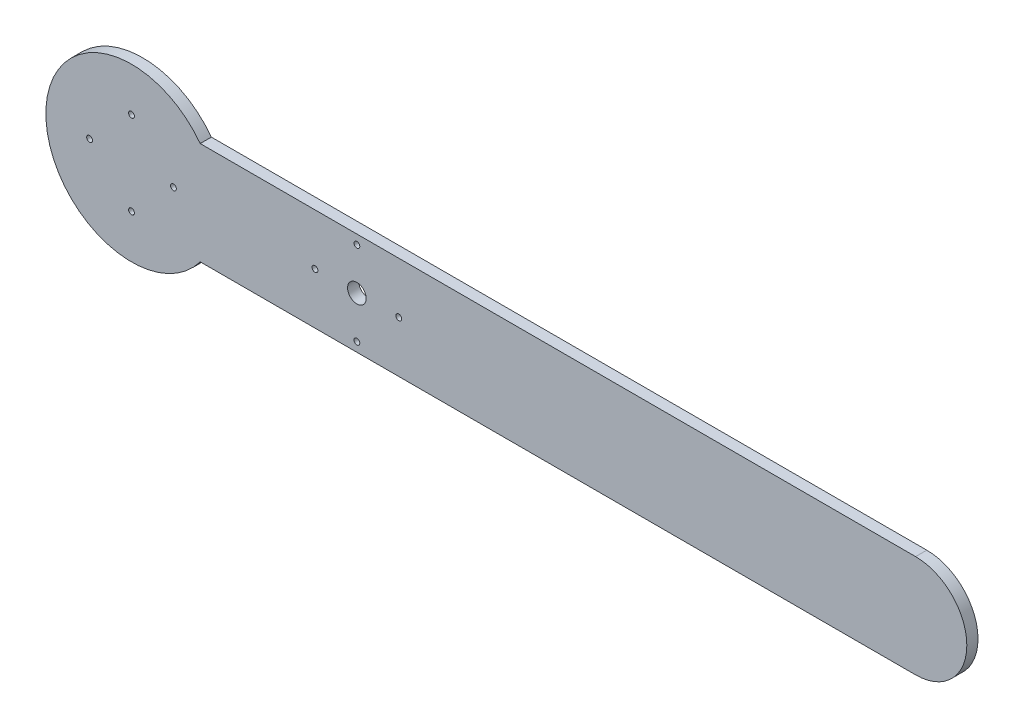
SolidWorks part; units mm, degrees
ref_plane "Front Plane" through (0, 0, 0) normal (0, 0, 1) x (1, 0, 0)
ref_plane "Top Plane" through (0, 0, 0) normal (0, 1, 0) x (1, 0, 0)
ref_plane "Right Plane" through (0, 0, 0) normal (1, 0, 0) x (0, 0, -1)
sketch "Sketch1" plane through (0, 0, 0) normal (0, 1, 0) x (1, 0, 0)
  line L0 (-47.5, -29.9135) -> (47.5, -29.9135) construction
  line L1 (-47.5, 56.6115) -> (47.5, 56.6115) construction
  line L2 (-47.5, 56.6115) -> (-47.5, -56.6115) construction
  line L3 (-47.5, -56.6115) -> (47.5, -56.6115) construction
  line L4 (47.5, 56.6115) -> (47.5, -56.6115) construction
  line L5 (-47.5, 56.6115) -> (47.5, -56.6115) construction
  line L6 (-47.5, -56.6115) -> (47.5, 56.6115) construction
  line L7 (-47.5, -23.9135) -> (47.5, -23.9135) construction
  line L8 (-47.5, 23.5865) -> (47.5, 23.5865) construction
  line L9 (47.5, 27.5865) -> (-47.5, 27.5865) construction
  line L10 (97.198, 47.5) -> (97.198, -47.5) construction
  line L11 (183.723, 47.5) -> (183.723, -47.5) construction
  line L12 (183.723, 47.5) -> (70.5, 47.5) construction
  line L13 (70.5, 47.5) -> (70.5, -47.5) construction
  line L14 (183.723, -47.5) -> (70.5, -47.5) construction
  line L15 (183.723, 47.5) -> (70.5, -47.5) construction
  line L16 (70.5, 47.5) -> (183.723, -47.5) construction
  line L17 (103.198, 47.5) -> (103.198, -47.5) construction
  line L18 (150.698, 47.5) -> (150.698, -47.5) construction
  line L19 (154.698, -47.5) -> (154.698, 47.5) construction
  line L20 (64.5, 102.0583) -> (64.5, -54.5) construction
  line L21 (47.5, -56.6115) -> (-169.5, -56.6115) construction
  line L22 (47.5, -56.6115) -> (47.5, -62.6115) construction
  line L23 (47.5, -62.6115) -> (-169.5, -62.6115) construction
  line L24 (-169.5, -56.6115) -> (-169.5, -62.6115) construction
  line L25 (64.5, -54.5) -> (327.1082, -54.5) construction
  line L26 (70.5, 108.0583) -> (70.5, -48.5) construction
  line L27 (70.5, -48.5) -> (327.1082, -48.5) construction
  line L28 (70.5, -48.5) -> (70.5, -54.5) construction
  line L29 (70.5, -48.5) -> (64.5, -48.5) construction
  line L30 (47.5, -56.6115) -> (47.5, -62.6115) construction
  line L31 (48.5, 17.5865) -> (48.5, -30) construction
  line L32 (48.5, -30) -> (54.5, -30) construction
  line L33 (54.5, -30) -> (54.5, 23.5865) construction
  line L34 (0, 0) -> (0, 56.6115) construction
  line L35 (-48.5, -30) -> (-54.5, -30) construction
  line L36 (-54.5, -30) -> (-54.5, 23.5865) construction
  line L37 (-48.5, 17.5865) -> (-48.5, -30) construction
  line L38 (54.5, 23.5865) -> (-54.5, 23.5865) construction
  line L39 (-48.5, 17.5865) -> (48.5, 17.5865) construction
  line L40 (48.5, 17.5865) -> (48.5, 23.5865) construction
  line L41 (70.5, 108.0583) -> (-59.952, 108.0583) construction
  line L42 (64.5, 102.0583) -> (-64.5, 102.0583) construction
  line L43 (-64.5, 102.0583) -> (-64.5, -48.5) construction
  line L44 (-64.5, -48.5) -> (-70.5, -48.5) construction
  line L45 (-70.5, -48.5) -> (-70.5, 98.5172) construction
  line L46 (-168.5, -56.6115) -> (-168.5, 23.9185) construction
  line L51 (-168.5, -62.6115) -> (-73.5, -62.6115) construction
  line L52 (-168.5, -62.6115) -> (-168.5, -89.3115) construction
  line L53 (-168.5, -89.3115) -> (-73.5, -89.3115) construction
  line L54 (-73.5, -62.6115) -> (-73.5, -89.3115) construction
  line L55 (-168.5, 23.9185) -> (-73.5, 23.9185) construction
  line L56 (-73.5, 23.9185) -> (-73.5, -56.6115) construction
  line L57 (-54.5, -23.9135) -> (-64.5, -23.9135) construction
  line L58 (54.5, -23.9135) -> (64.5, -23.9135) construction
  line L59 (64.5, 102.0583) -> (64.5, 108.0583) construction
  point P0 (0, 0)
  point P17 (127.1115, 0)
  dimension "D1" = 113.223
  dimension "D2" = 95
  dimension "D3" = 6
  dimension "D4" = 26.698
  dimension "D5" = 4
  dimension "D6" = 57.5
  dimension "D7" = 29.025
  dimension "D8" = 6
  dimension "D9" = 95
  dimension "D10" = 6
  dimension "D11" = 26.698
  dimension "D12" = 4
  dimension "D13" = 29.025
  dimension "D14" = 57.5
  dimension "D15" = 30
  dimension "D16" = 1
  dimension "D17" = 1
  dimension "D18" = 10
  dimension "D19" = 26.7
  dimension "D20" = 80.53
  dimension "D21" = 3
  dimension "D22" = 1
sketch "Sketch2" plane through (0, 0, 0) normal (0, 0, 1) x (1, 0, 0)
  line L0 (-47.5, 0) -> (47.5, 0) construction
  line L1 (-47.5, -50) -> (47.5, -50) construction
  line L2 (-47.5, -50) -> (-47.5, 50) construction
  line L3 (-47.5, 50) -> (47.5, 50) construction
  line L4 (47.5, -50) -> (47.5, 50) construction
  line L5 (-47.5, -50) -> (47.5, 50) construction
  line L6 (-47.5, 50) -> (47.5, -50) construction
  line L11 (0, 0) -> (0, 22.5) construction
  line L12 (-168.5, 0) -> (-73.5, 0) construction
  line L13 (-168.5, 0) -> (-73.5, 0) construction
  line L14 (300, 27.5) -> (-84.1252, 27.5)
  line L16 (-84.1252, -27.5) -> (300, -27.5)
  line L19 (-84.1252, -27.5) -> (-84.1252, 27.5) construction
  circle A0 centre (0, 0) radius 22.5 construction
  circle A1 centre (0, 22.5) radius 1.5635
  circle A2 centre (22.5, 0) radius 1.5635
  circle A3 centre (0, -22.5) radius 1.5635
  circle A4 centre (-22.5, 0) radius 1.5635
  circle A5 centre (-143.5, 0) radius 1.5635 construction
  circle A6 centre (-121, 0) radius 22.5 construction
  circle A7 centre (-121, 22.5) radius 1.5635 construction
  circle A8 centre (-98.5, 0) radius 1.5635 construction
  circle A9 centre (-121, -22.5) radius 1.5635 construction
  arc A11 (-84.1252, 27.5) -> (-84.1252, -27.5) centre (-121, 0) ccw
  circle A13 centre (-121, -22.5) radius 1.5635
  circle A14 centre (-143.5, 0) radius 1.5635
  circle A15 centre (-121, 22.5) radius 1.5635
  circle A16 centre (-98.5, 0) radius 1.5635
  arc A18 (300, 27.5) -> (300, -27.5) centre (300, 0) cw
  circle A19 centre (0, 0) radius 5
  point P0 (0, 0)
  point P15 (0, 0)
  point P18 (0, 0)
  point P21 (0, 0)
  point P24 (0, 0)
  point P39 (-47.5, 51)
  point P40 (-47.5, -51)
  point P57 (-121, 0)
  dimension "D3" = 45
  dimension "D4" = 3.127
  dimension "D7" = 5
  dimension "D8" = 46
  dimension "D11" = 10
  dimension "D1" = 100
  dimension "D2" = 95
  dimension "D9" = 1
  dimension "D10" = 300
  dimension "D6" = 2
  dimension "D5" = 4
  dimension "D12" = 4
extrude "Boss-Extrude1" add sketch "Sketch2" along normal up to vertex (62.6115 mm away) from vertex at 56.6115 starting at point (47.5, 0, 56.6115)
sketch "Sketch3" [suppressed] plane through (0, 0, 0) normal (0, 1, 0) x (1, 0, 0)
  line L0 (-48.5, -30) -> (-54.5, -30) construction
  line L1 (-48.5, 17.5865) -> (-48.5, -30) construction
  line L2 (-54.5, -30) -> (-54.5, 23.5865) construction
  line L3 (-48.5, 17.5865) -> (48.5, 17.5865) construction
  line L4 (54.5, 23.5865) -> (-54.5, 23.5865) construction
  line L5 (54.5, -30) -> (54.5, 23.5865) construction
  line L6 (48.5, 17.5865) -> (48.5, -30) construction
  line L7 (48.5, -30) -> (54.5, -30) construction
  line L8 (-48.5, -30) -> (-54.5, -30)
  line L9 (-48.5, 17.5865) -> (-48.5, -30)
  line L10 (-54.5, -30) -> (-54.5, 23.5865)
  line L11 (-48.5, 17.5865) -> (48.5, 17.5865)
  line L12 (54.5, 23.5865) -> (-54.5, 23.5865)
  line L13 (54.5, -30) -> (54.5, 23.5865)
  line L14 (48.5, 17.5865) -> (48.5, -30)
  line L15 (48.5, -30) -> (54.5, -30)
extrude "Boss-Extrude2" [suppressed] add sketch "Sketch3" along normal up to vertex and the other way up to vertex
sketch "Sketch4" [suppressed] plane through (0, 0, -17.5865) normal (0, 0, 1) x (1, 0, 0)
  line L1 (30, -45) -> (-30, -45) construction
  line L2 (30, -45) -> (30, 45) construction
  line L3 (30, 45) -> (-30, 45) construction
  line L4 (-30, -45) -> (-30, 45) construction
  line L5 (30, -45) -> (-30, 45) construction
  line L6 (30, 45) -> (-30, -45) construction
  circle A0 centre (0, 0) radius 46.25
  circle A1 centre (-30, 45) radius 2.25
  circle A2 centre (30, 45) radius 2.25
  circle A3 centre (30, -45) radius 2.25
  circle A4 centre (-30, -45) radius 2.25
  dimension "D1" = 92.5
  dimension "D4" = 4.5
  dimension "D2" = 90
  dimension "D3" = 60
extrude "Cut-Extrude1" [suppressed] cut sketch "Sketch4" against normal through all
sketch "Sketch5" [suppressed] plane through (54.5, 0, 0) normal (1, 0, 0) x (0, 0, -1)
  circle A0 centre (0, 0) radius 14.2875
  point P0 (0, 0)
  dimension "D1" = 28.575
extrude "Cut-Extrude2" [suppressed] cut sketch "Sketch5" against normal through all
